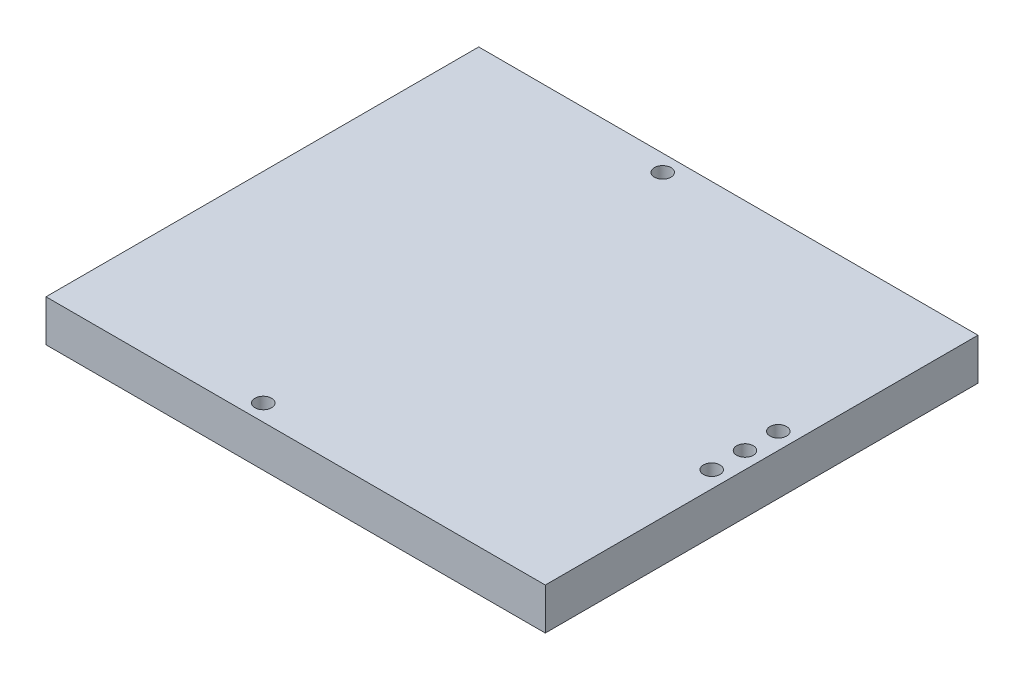
SolidWorks part; units mm, degrees
ref_plane "Front Plane" through (0, 0, 0) normal (0, 0, 1) x (1, 0, 0)
ref_plane "Top Plane" through (0, 0, 0) normal (0, 1, 0) x (1, 0, 0)
ref_plane "Right Plane" through (0, 0, 0) normal (1, 0, 0) x (0, 0, -1)
sketch "Sketch1" plane through (0, 0, 0) normal (0, 1, 0) x (1, 0, 0)
  line L0 (60, 0) -> (60, 104) construction
  line L1 (0, 0) -> (120, 0)
  line L2 (0, 0) -> (0, 104)
  line L3 (0, 104) -> (120, 104)
  line L4 (120, 0) -> (120, 104)
  line L5 (0, 52) -> (120, 52) construction
  circle A0 centre (116, 52) radius 2
  circle A1 centre (116, 60) radius 2
  circle A2 centre (116, 44) radius 2
  circle A3 centre (48.2232, 4) radius 2
  circle A4 centre (48.2232, 100) radius 2
  dimension "D3" = 4
  dimension "D7" = 4
  dimension "D8" = 4
  dimension "D1" = 120
  dimension "D2" = 104
  dimension "D4" = 8
  dimension "D5" = 4
  dimension "D6" = 4
  dimension "D9" = 4
  dimension "D10" = 78.7
extrude "Boss-Extrude2" add sketch "Sketch1" along normal blind 10
